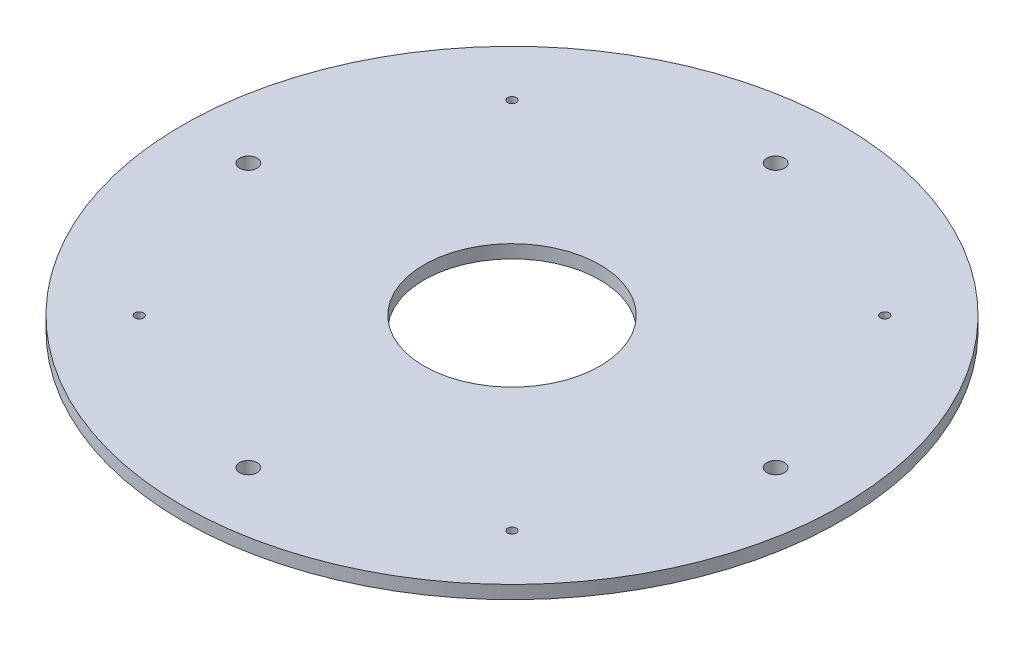
SolidWorks part; units mm, degrees
ref_plane "前基準面" through (0, 0, 0) normal (0, 0, 1) x (1, 0, 0)
ref_plane "上基準面" through (0, 0, 0) normal (0, 1, 0) x (1, 0, 0)
ref_plane "右基準面" through (0, 0, 0) normal (1, 0, 0) x (0, 0, -1)
sketch "草圖1" plane through (0, 0, 0) normal (0, 1, 0) x (1, 0, 0)
  circle A0 centre (0, 0) radius 75
  circle A1 centre (0, 0) radius 20
  dimension "D1" = 150
  dimension "D2" = 40
extrude "填料-伸長1" add sketch "草圖1" along normal blind 3
sketch "草圖2" plane through (0, 3, 0) normal (0, 1, 0) x (1, 0, 0)
  line L0 (0, 0) -> (42.4264, 42.4264)
  circle A1 centre (42.4264, 42.4264) radius 1
  dimension "D2" = 2
  dimension "D1" = 60
extrude "除料-伸長3" cut sketch "草圖2" against normal blind 10
pattern_circular "環狀複製排列3" count 4 over 360 about axis through (0, 0, 0) along (0, 1, 0) of "除料-伸長3"
sketch "草圖3" plane through (0, 3, 0) normal (0, 1, 0) x (1, 0, 0)
  line L0 (0, 0) -> (-60, 0)
  circle A0 centre (-60, 0) radius 2
  dimension "D2" = 4
  dimension "D1" = 60
extrude "除料-伸長4" cut sketch "草圖3" against normal blind 10
pattern_circular "環狀複製排列4" count 4 over 360 about axis through (0, 0, 0) along (0, 1, 0) of "除料-伸長4"
